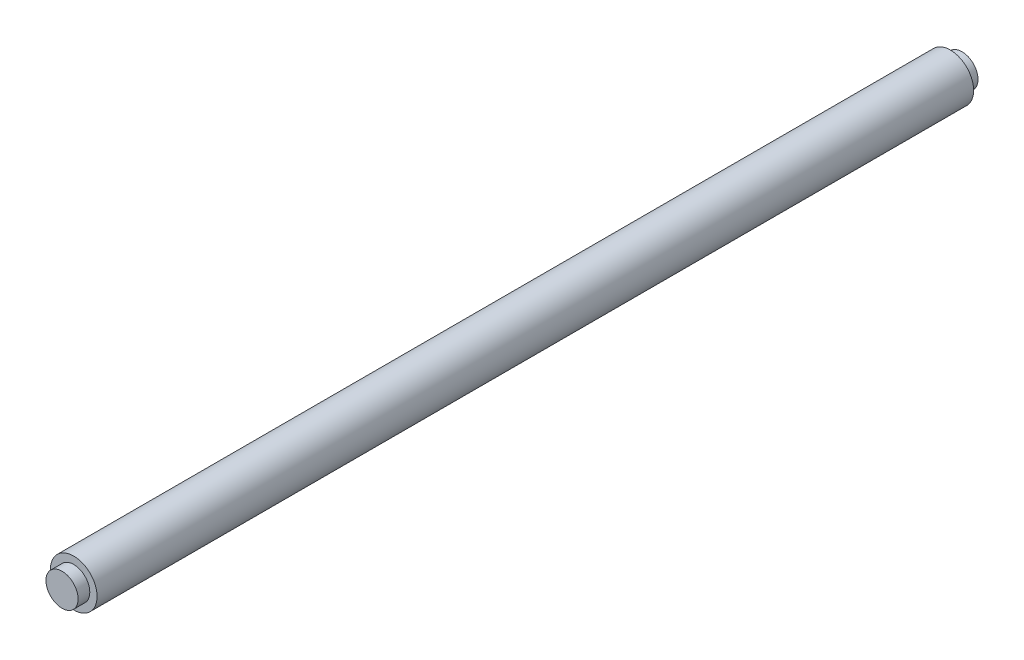
SolidWorks part; units mm, degrees
ref_plane "Alzado" through (0, 0, 0) normal (0, 0, 1) x (1, 0, 0)
ref_plane "Planta" through (0, 0, 0) normal (0, 1, 0) x (1, 0, 0)
ref_plane "Vista lateral" through (0, 0, 0) normal (1, 0, 0) x (0, 0, -1)
sketch "Croquis1" plane through (0, 0, 0) normal (0, 0, 1) x (1, 0, 0)
  circle A0 centre (0, 0) radius 2
  point P2 (0, 0)
  dimension "D1" = 4
extrude "Saliente-Extruir1" add sketch "Croquis1" along normal blind 75
sketch "Croquis2" plane through (0, 0, 75) normal (0, 0, 1) x (1, 0, 0)
  circle A0 centre (0, 0) radius 1.375
  dimension "D1" = 2.75
extrude "Saliente-Extruir2" add sketch "Croquis2" along normal blind 1
sketch "Croquis4" plane through (0, 0, 0) normal (0, 0, -1) x (-1, 0, 0)
  circle A0 centre (0, 0) radius 1.375
  dimension "D1" = 2.75
extrude "Saliente-Extruir3" add sketch "Croquis4" along normal blind 1
